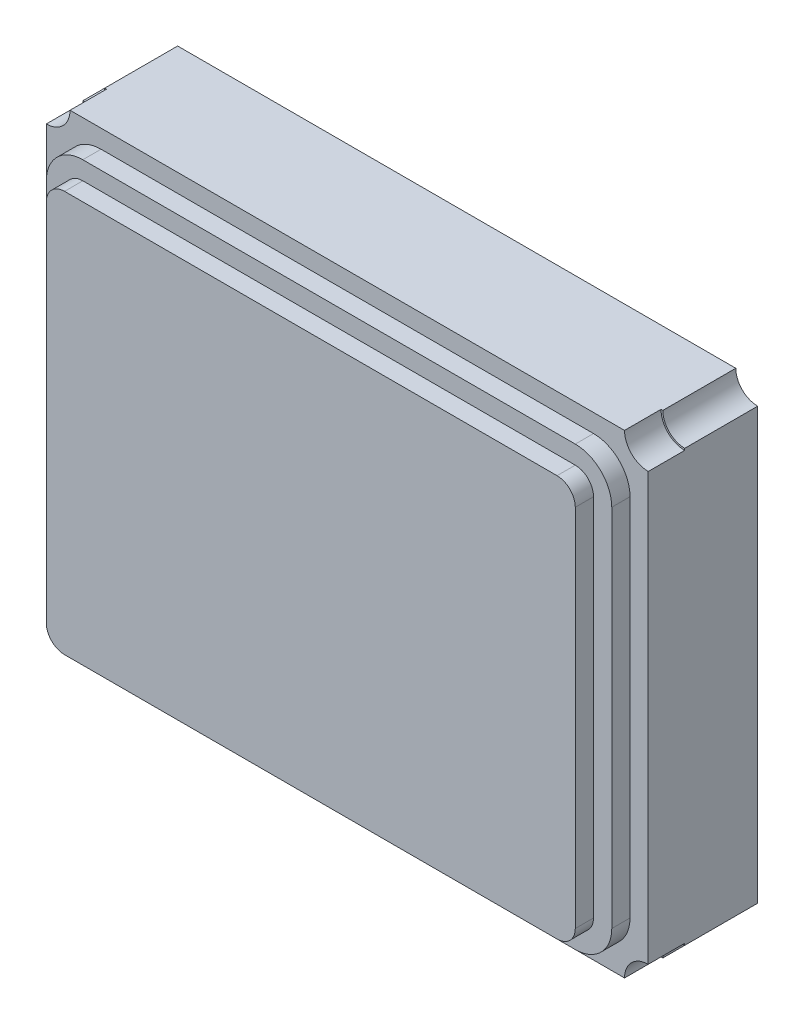
SolidWorks part; units mm, degrees
ref_plane "Top Plane" through (0, 0, 0) normal (0, 0, 1) x (1, 0, 0)
ref_plane "Front Plane" through (0, 0, 0) normal (0, 1, 0) x (1, 0, 0)
ref_plane "Right Plane" through (0, 0, 0) normal (1, 0, 0) x (0, 0, -1)
sketch "Sketch1" plane through (0, 0, 0) normal (0, 0, 1) x (1, 0, 0)
  line L1 (-1.65, -1.3) -> (1.65, -1.3)
  line L2 (-1.65, -1.3) -> (-1.65, 1.3)
  line L3 (-1.65, 1.3) -> (1.65, 1.3)
  line L4 (1.65, -1.3) -> (1.65, 1.3)
  line L5 (-1.65, -1.3) -> (1.65, 1.3) construction
  line L6 (-1.65, 1.3) -> (1.65, -1.3) construction
  arc A0 (-1.65, 1.18) -> (-1.53, 1.3) centre (-1.65, 1.3) ccw
  arc A1 (1.53, 1.3) -> (1.65, 1.18) centre (1.65, 1.3) ccw
  arc A2 (1.65, -1.18) -> (1.53, -1.3) centre (1.65, -1.3) ccw
  arc A3 (-1.65, -1.18) -> (-1.53, -1.3) centre (-1.65, -1.3) cw
  point P0 (0, 0)
  dimension "D1" = 0.12
  dimension "D2" = 3.3
  dimension "D3" = 2.6
extrude "Boss-Extrude1" add sketch "Sketch1" along normal blind 0.8 contours L2 A3 L1 A2 L4 A1 L3 A0
sketch "Sketch2" plane through (0, 0, 0.8) normal (0, 0, 1) x (1, 0, 0)
  line L0 (0, -1.1) -> (0, 1.1) construction
  line L1 (-1.35, -1.1) -> (1.35, -1.1)
  line L2 (-1.45, -1) -> (-1.45, 1)
  line L3 (-1.35, 1.1) -> (1.35, 1.1)
  line L4 (1.45, -1) -> (1.45, 1)
  line L7 (-1.45, 0) -> (1.45, 0) construction
  arc A0 (1.35, -1.1) -> (1.45, -1) centre (1.35, -1) ccw
  arc A1 (-1.35, -1.1) -> (-1.45, -1) centre (-1.35, -1) cw
  arc A2 (-1.45, 1) -> (-1.35, 1.1) centre (-1.35, 1) cw
  arc A3 (1.35, 1.1) -> (1.45, 1) centre (1.35, 1) cw
  point P0 (0, 0)
  dimension "D1" = 0.1
  dimension "D2" = 2.9
  dimension "D3" = 2.2
extrude "Cut-Extrude1" cut sketch "Sketch2" against normal blind 0.1 flip side to cut
sketch "Sketch4" plane through (0, 0, 0.8) normal (0, 0, 1) x (1, 0, 0)
  line L0 (0, -1.2) -> (0, 1.2) construction
  line L1 (-1.35, -1.2) -> (1.35, -1.2)
  line L2 (-1.55, -1) -> (-1.55, 1)
  line L3 (-1.35, 1.2) -> (1.35, 1.2)
  line L4 (1.55, -1) -> (1.55, 1)
  line L7 (-1.55, 0) -> (1.55, 0) construction
  arc A0 (1.35, -1.2) -> (1.55, -1) centre (1.35, -1) ccw
  arc A1 (-1.35, -1.2) -> (-1.55, -1) centre (-1.35, -1) cw
  arc A2 (-1.55, 1) -> (-1.35, 1.2) centre (-1.35, 1) cw
  arc A3 (1.35, 1.2) -> (1.55, 1) centre (1.35, 1) cw
  point P0 (0, 0)
  dimension "D1" = 0.2
  dimension "D2" = 3.1
  dimension "D3" = 2.4
extrude "Cut-Extrude2" cut sketch "Sketch4" against normal blind 0.2 flip side to cut
sketch "Sketch5" plane through (0, 0, 0.6) normal (0, 0, 1) x (1, 0, 0)
  line L0 (1.65, -1.17) -> (1.65, -1.3)
  line L1 (-1.65, -1.3) -> (1.65, -1.3) construction
  line L2 (-1.65, -1.3) -> (-1.65, 1.3) construction
  line L3 (-1.65, 1.3) -> (1.65, 1.3) construction
  line L4 (1.65, -1.3) -> (1.65, 1.3) construction
  line L5 (-1.65, -1.3) -> (1.65, 1.3) construction
  line L6 (-1.65, 1.3) -> (1.65, -1.3) construction
  line L7 (1.65, -1.3) -> (1.52, -1.3)
  line L8 (-1.65, -1.17) -> (-1.65, -1.3)
  line L9 (-1.65, -1.3) -> (-1.52, -1.3)
  line L10 (-1.52, 1.3) -> (-1.65, 1.3)
  line L11 (-1.65, 1.3) -> (-1.65, 1.17)
  line L12 (1.52, 1.3) -> (1.65, 1.3)
  line L13 (1.65, 1.3) -> (1.65, 1.17)
  arc A0 (-1.65, 1.17) -> (-1.52, 1.3) centre (-1.65, 1.3) ccw
  arc A1 (1.52, 1.3) -> (1.65, 1.17) centre (1.65, 1.3) ccw
  arc A2 (1.65, -1.17) -> (1.52, -1.3) centre (1.65, -1.3) ccw
  arc A3 (-1.65, -1.17) -> (-1.52, -1.3) centre (-1.65, -1.3) cw
  point P0 (0, 0)
  dimension "D1" = 0.13
  dimension "D2" = 3.3
  dimension "D3" = 2.6
extrude "Cut-Extrude5" cut sketch "Sketch5" against normal blind 0.2
